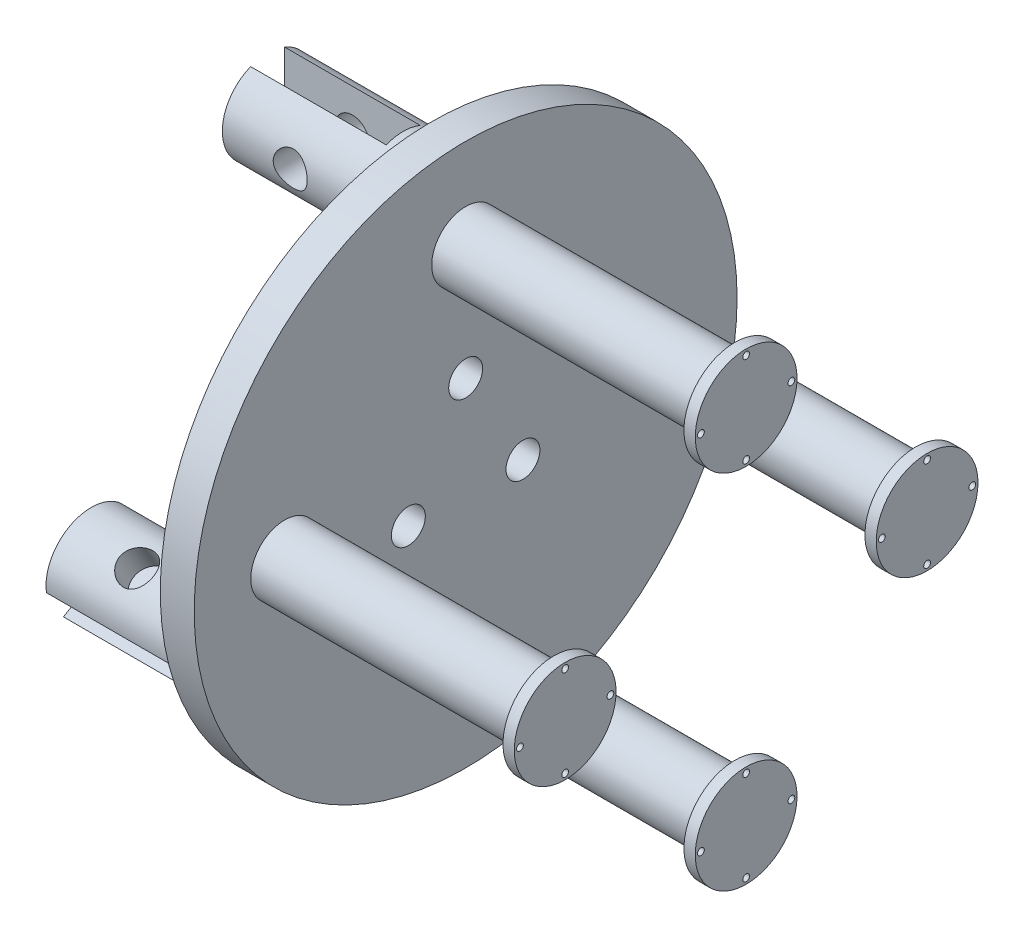
SolidWorks part; units mm, degrees
ref_plane "前视基准面" through (0, 0, 0) normal (0, 0, 1) x (1, 0, 0)
ref_plane "上视基准面" through (0, 0, 0) normal (0, 1, 0) x (1, 0, 0)
ref_plane "右视基准面" through (0, 0, 0) normal (1, 0, 0) x (0, 0, -1)
sketch "草图2" plane through (0, 0, 0) normal (1, 0, 0) x (0, 0, -1)
  circle A0 centre (0, 0) radius 120
  dimension "D1" = 240
extrude "凸台-拉伸1" add sketch "草图2" along normal blind 15
sketch "草图3" plane through (0, 0, 0) normal (-1, 0, 0) x (0, 0, 1)
  circle A0 centre (0, 0) radius 29.25 construction
  circle A1 centre (0, 29.25) radius 7.5
  circle A2 centre (25.3312, -14.625) radius 7.5
  circle A3 centre (-25.3312, -14.625) radius 7.5
  point P11 (0, 0)
  dimension "D1" = 58.5
  dimension "D2" = 15
  dimension "D3" = 3
extrude "切除-拉伸1" cut sketch "草图3" against normal through all both and the other way through all
sketch "草图4" plane through (15, 0, 0) normal (1, 0, 0) x (0, 0, -1)
  line L0 (-80, 0) -> (103.2758, 0) construction
  circle A0 centre (0, 0) radius 80 construction
  circle A1 centre (0, 80) radius 15
  circle A3 centre (80, 0) radius 15
  circle A4 centre (0, -80) radius 15
  circle A5 centre (-80, 0) radius 15
  point P16 (0, 0)
  dimension "D1" = 160
  dimension "D2" = 30
  dimension "D3" = 4
extrude "凸台-拉伸2" add sketch "草图4" along normal blind 119
sketch "草图5" plane through (0, 0, 0) normal (-1, 0, 0) x (0, 0, 1)
  circle A0 centre (0, 0) radius 90 construction
  circle A1 centre (0, 90) radius 20
  circle A2 centre (77.9423, -45) radius 20
  circle A3 centre (-77.9423, -45) radius 20
  point P3 (0, 90)
  point P12 (0, 0)
  point P18 (0, 0)
  dimension "D1" = 180
  dimension "D2" = 40
  dimension "D3" = 3
extrude "凸台-拉伸3" add sketch "草图5" along normal blind 72.58
sketch "草图7" plane through (-72.58, 0, 0) normal (-1, 0, 0) x (0, 0, 1)
  line L0 (51.8445, -38.5927) -> (130.6253, -84.0768)
  line L1 (130.6253, -84.0768) -> (138.1253, -71.0864)
  line L2 (138.1253, -71.0864) -> (59.3445, -25.6023)
  line L3 (59.3445, -25.6023) -> (51.8445, -38.5927)
  line L4 (-51.8445, -38.5927) -> (-59.3445, -25.6023)
  line L5 (-59.3445, -25.6023) -> (-138.1253, -71.0864)
  line L6 (-138.1253, -71.0864) -> (-130.6253, -84.0768)
  line L7 (-130.6253, -84.0768) -> (-51.8445, -38.5927)
  line L8 (-7.5, 64.195) -> (7.5, 64.195)
  line L9 (7.5, 64.195) -> (7.5, 155.1633)
  line L10 (7.5, 155.1633) -> (-7.5, 155.1633)
  line L11 (-7.5, 155.1633) -> (-7.5, 64.195)
  line L12 (77.9423, -45) -> (158.7712, -91.6666) construction
  line L13 (0, 21.75) -> (0, 177.5242) construction
  circle A0 centre (0, 29.25) radius 7.5 construction
  point P15 (0, 0)
  dimension "D2" = 15
  dimension "D1" = 3
extrude "切除-拉伸3" cut sketch "草图7" against normal blind 60
sketch "草图8" plane through (0, 6.4952, 3.75) normal (0, -0.866, -0.5) x (1, 0, 0)
  line L0 (-72.58, 90) -> (42.1087, 90) construction
  line L1 (-72.58, 108.5405) -> (-72.58, 71.4595) construction
  line L2 (-42.58, 108.5405) -> (-42.58, 49.8516) construction
  line L3 (-12.58, 108.5405) -> (-72.58, 108.5405) construction
  circle A0 centre (-42.58, 90) radius 7.5
  dimension "D1" = 15
extrude "切除-拉伸4" cut sketch "草图8" against normal through all both and the other way through all
sketch "草图9" plane through (0, -6.4952, 3.75) normal (0, 0.866, -0.5) x (1, 0, 0)
  line L0 (-42.58, 71.4595) -> (-42.58, 175.2755) construction
  line L1 (-72.58, 71.4595) -> (-12.58, 71.4595) construction
  line L2 (-72.58, 90) -> (77.0342, 90) construction
  line L3 (-72.58, 108.5405) -> (-72.58, 71.4595) construction
  circle A0 centre (-42.58, 90) radius 7.5
  dimension "D1" = 15
extrude "切除-拉伸5" cut sketch "草图9" against normal through all both and the other way through all
sketch "草图10" plane through (0, 0, -7.5) normal (0, 0, 1) x (1, 0, 0)
  line L0 (-42.58, 108.5405) -> (-42.58, 21.1708) construction
  line L1 (-12.58, 108.5405) -> (-72.58, 108.5405) construction
  line L2 (-72.58, 90) -> (133.2607, 90) construction
  line L3 (-72.58, 108.5405) -> (-72.58, 71.4595) construction
  circle A0 centre (-42.58, 90) radius 7.5
  dimension "D1" = 15
extrude "切除-拉伸6" cut sketch "草图10" against normal through all both and the other way through all
sketch "草图11" plane through (134, 0, 0) normal (1, 0, 0) x (0, 0, -1)
  circle A0 centre (-80, 0) radius 22.5
  circle A1 centre (0, 80) radius 22.5
  circle A2 centre (80, 0) radius 22.5
  circle A3 centre (0, -80) radius 22.5
  point P12 (0, 0)
  dimension "D1" = 45
  dimension "D2" = 4
extrude "凸台-拉伸4" add sketch "草图11" along normal blind 5
sketch "草图12" plane through (139, 0, 0) normal (1, 0, 0) x (0, 0, -1)
  circle A0 centre (-80, 0) radius 20 construction
  circle A1 centre (-60, 0) radius 1.5
  circle A2 centre (-80, -20) radius 1.5
  circle A3 centre (-100, 0) radius 1.5
  circle A4 centre (-80, 20) radius 1.5
  circle A5 centre (0, 80) radius 20 construction
  circle A6 centre (80, 0) radius 20 construction
  circle A7 centre (0, -80) radius 20 construction
  circle A8 centre (0, 60) radius 1.5
  circle A9 centre (60, 0) radius 1.5
  circle A10 centre (0, -60) radius 1.5
  circle A11 centre (20, 80) radius 1.5
  circle A12 centre (80, -20) radius 1.5
  circle A13 centre (-20, -80) radius 1.5
  circle A14 centre (0, 100) radius 1.5
  circle A15 centre (100, 0) radius 1.5
  circle A16 centre (0, -100) radius 1.5
  circle A17 centre (-20, 80) radius 1.5
  circle A18 centre (80, 20) radius 1.5
  circle A19 centre (20, -80) radius 1.5
  point P5 (-100, 0)
  point P6 (0, 0)
  point P7 (0, 0)
  point P14 (-80, 0)
  point P21 (0, 0)
  point P28 (0, 0)
  point P35 (0, 0)
  point P42 (0, 0)
  point P49 (0, 0)
  point P50 (0, 0)
  point P52 (0, 0)
  point P54 (0, 0)
  dimension "D1" = 40
  dimension "D2" = 3
  dimension "D3" = 4
  dimension "D4" = 4
  dimension "D5" = 4
  dimension "D6" = 4
  dimension "D7" = 4
  dimension "D8" = 4
extrude "切除-拉伸7" cut sketch "草图12" against normal blind 10
